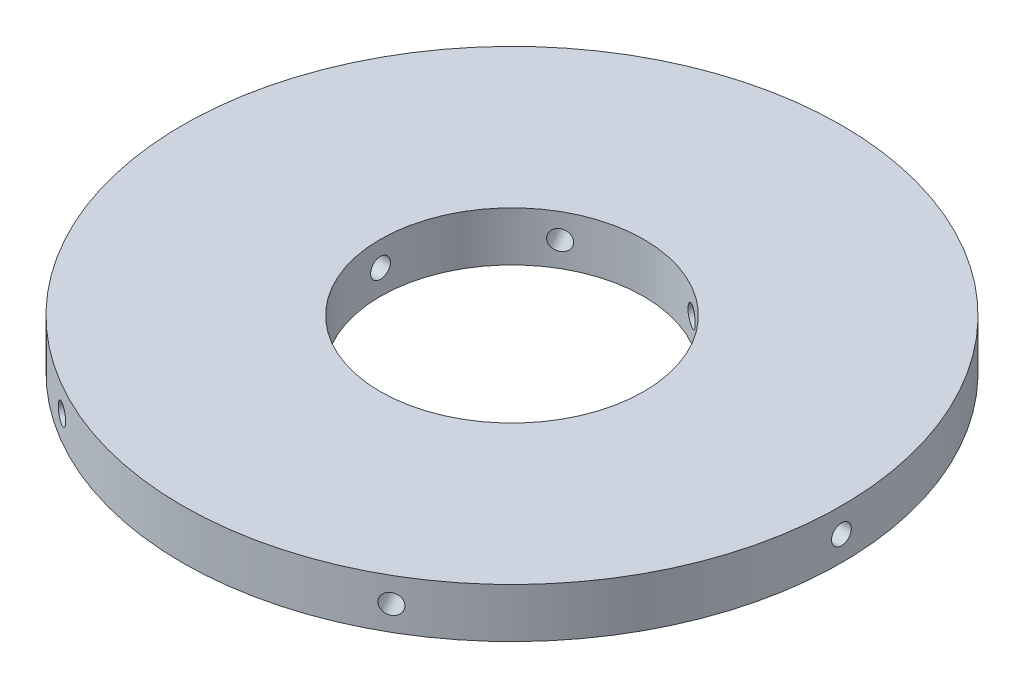
SolidWorks part; units mm, degrees
ref_plane "Front Plane" through (0, 0, 0) normal (0, 0, 1) x (1, 0, 0)
ref_plane "Top Plane" through (0, 0, 0) normal (0, 1, 0) x (1, 0, 0)
ref_plane "Right Plane" through (0, 0, 0) normal (1, 0, 0) x (0, 0, -1)
sketch "Sketch1" plane through (0, 0, 0) normal (0, 1, 0) x (1, 0, 0)
  line L0 (0, 0) -> (0, 87.698) construction
  line L1 (0, 0) -> (-128.1213, 0) construction
  circle A0 centre (0, 0) radius 100
  circle A1 centre (0, 0) radius 40
  dimension "D1" = 200
  dimension "D2" = 80
extrude "Boss-Extrude1" add sketch "Sketch1" along normal blind 15
sketch "Sketch2" plane through (0, 0, 0) normal (1, 0, 0) x (0, 0, -1)
  line L0 (100, 7.5) -> (-100, 7.5) construction
  line L1 (100, 0) -> (100, 15) construction
  line L2 (-100, 15) -> (-100, 0) construction
  circle A0 centre (0, 7.5) radius 3
  dimension "D1" = 6
extrude "Cut-Extrude1" cut sketch "Sketch2" against normal through all
pattern_circular "CirPattern1" count 6 over 360 about axis through (0, 15, 0) along (0, 1, 0) of "Cut-Extrude1"
equation "\"holes\"=6"
equation "\"D1@CirPattern1\"=\"holes\""
